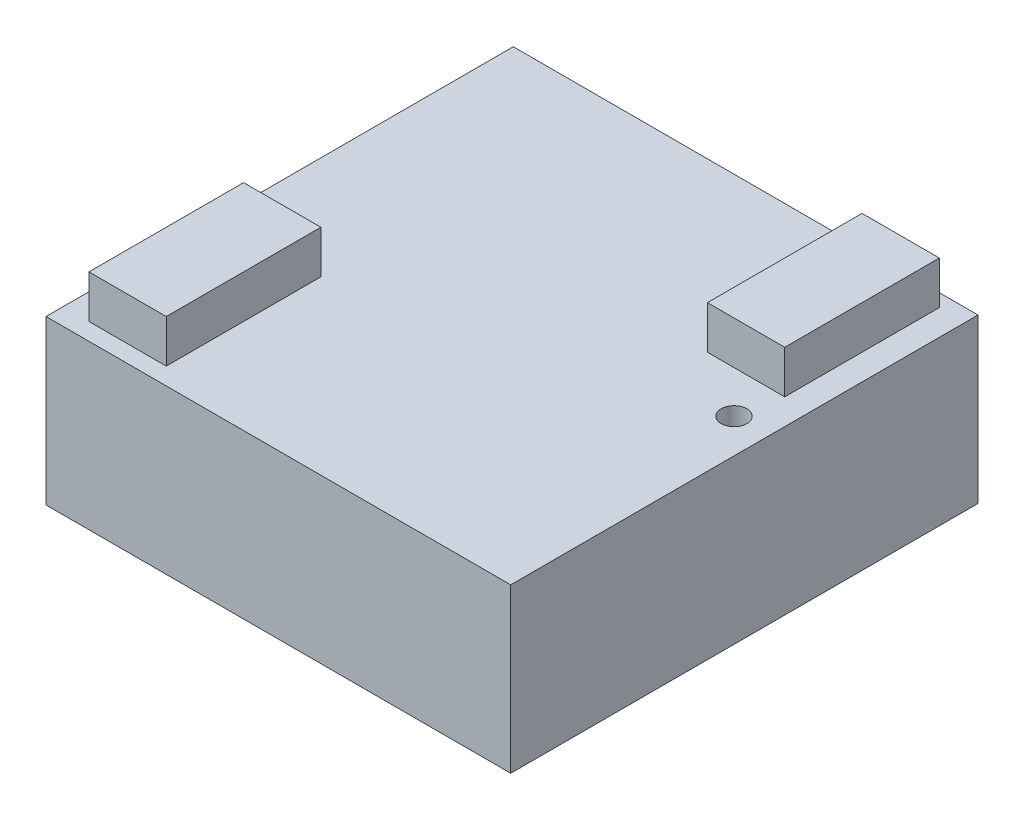
SolidWorks part; units mm, degrees
material "Epoxy, renforcé"
ref_plane "Plan de face" through (0, 0, 0) normal (0, 0, 1) x (1, 0, 0)
ref_plane "Plan de dessus" through (0, 0, 0) normal (0, 1, 0) x (1, 0, 0)
ref_plane "Plan de droite" through (0, 0, 0) normal (1, 0, 0) x (0, 0, -1)
sketch "Esquisse1" plane through (0, 0, 0) normal (0, 1, 0) x (1, 0, 0)
  line L1 (0, 0) -> (54.1, 0)
  line L2 (0, 0) -> (0, 54.4)
  line L3 (0, 54.4) -> (54.1, 54.4)
  line L4 (54.1, 0) -> (54.1, 54.4)
  dimension "D1" = 54.4
  dimension "D2" = 54.1
extrude "Boss.-Extru.1" add sketch "Esquisse1" along normal blind 19
sketch "Esquisse2" plane through (0, 0, 0) normal (0, -1, 0) x (1, 0, 0)
  line L0 (0, -54.4) -> (0, 0) construction
  line L1 (17, -34.4) -> (37, -34.4)
  line L2 (17, -34.4) -> (17, -22.4)
  line L3 (17, -22.4) -> (37, -22.4)
  line L4 (37, -34.4) -> (37, -22.4)
  line L5 (54.1, -54.4) -> (0, -54.4) construction
  point P4 (27, -34.4)
  point P7 (37, -28.4)
  dimension "D1" = 20
  dimension "D2" = 12
  dimension "D3" = 27
  dimension "D4" = 26
extrude "Boss.-Extru.2" add sketch "Esquisse2" along normal blind 15
sketch "Esquisse3" plane through (0, 19, 0) normal (0, 1, 0) x (1, 0, 0)
  line L0 (0, 0) -> (54.1, 0) construction
  line L1 (42.1, 52.9) -> (51.1, 52.9)
  line L2 (42.1, 52.9) -> (42.1, 34.9)
  line L3 (42.1, 34.9) -> (51.1, 34.9)
  line L4 (51.1, 52.9) -> (51.1, 34.9)
  line L5 (3, 20) -> (12, 20)
  line L6 (3, 20) -> (3, 2)
  line L7 (3, 2) -> (12, 2)
  line L8 (12, 20) -> (12, 2)
  line L9 (54.1, 54.4) -> (0, 54.4) construction
  line L10 (54.1, 0) -> (54.1, 54.4) construction
  line L11 (0, 54.4) -> (0, 0) construction
  dimension "D1" = 18
  dimension "D2" = 2
  dimension "D3" = 1.5
  dimension "D4" = 3
  dimension "D5" = 9
  dimension "D6" = 3
extrude "Boss.-Extru.3" add sketch "Esquisse3" along normal blind 5
sketch "Esquisse4" plane through (0, 0, 0) normal (0, -1, 0) x (1, 0, 0)
  line L0 (54.1, 0) -> (54.1, -54.4) construction
  line L1 (0, 0) -> (54.1, 0) construction
  line L2 (54.1, -54.4) -> (0, -54.4) construction
  circle A0 centre (50.1, -30) radius 1.5
  dimension "D1" = 3
  dimension "D2" = 4
  dimension "D3" = 30
  dimension "D4" = 24.4
extrude "Enlèv. mat.-Extru.1" cut sketch "Esquisse4" against normal through all
